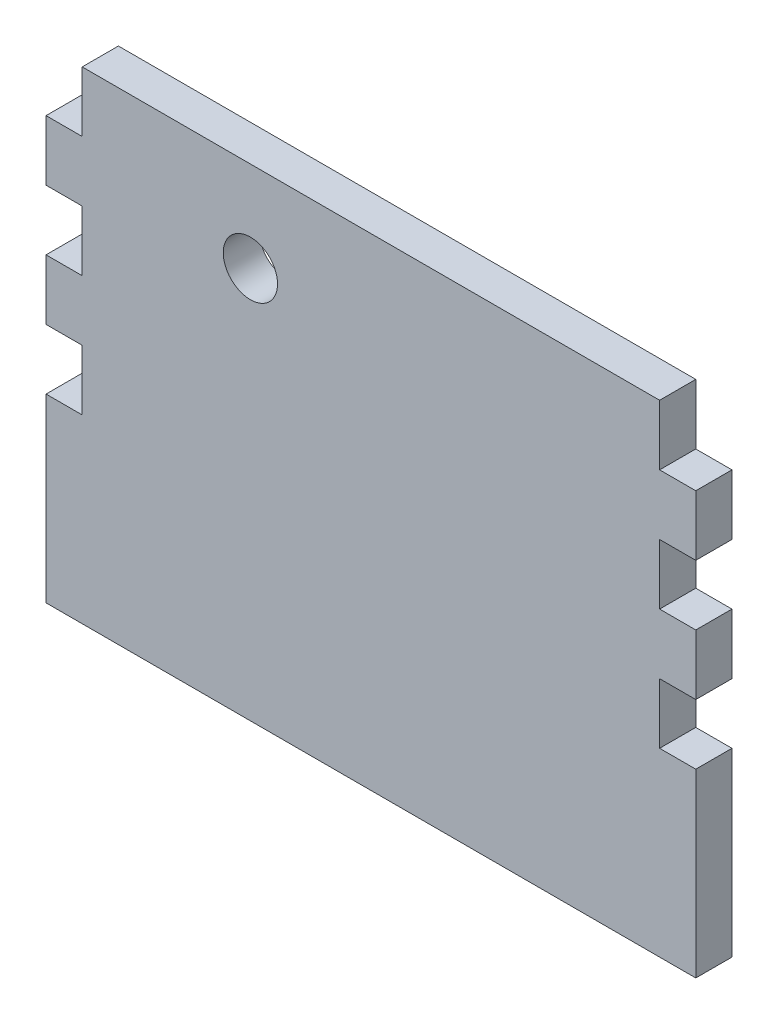
SolidWorks part; units mm, degrees
ref_plane "Front Plane" through (0, 0, 0) normal (0, 0, 1) x (1, 0, 0)
ref_plane "Top Plane" through (0, 0, 0) normal (0, 1, 0) x (1, 0, 0)
ref_plane "Right Plane" through (0, 0, 0) normal (1, 0, 0) x (0, 0, -1)
sketch "Sketch1" plane through (0, 0, 0) normal (0, 0, 1) x (1, 0, 0)
  line L1 (-26.945, 20) -> (26.945, 20)
  line L2 (-26.945, 20) -> (-26.945, -20)
  line L3 (-26.945, -20) -> (26.945, -20)
  line L4 (26.945, 20) -> (26.945, -20)
  line L5 (-26.945, 20) -> (26.945, -20) construction
  line L6 (-26.945, -20) -> (26.945, 20) construction
  point P0 (0, 0)
  dimension "D1" = 53.89
  dimension "D2" = 40
extrude "Boss-Extrude1" add sketch "Sketch1" along normal blind 3 contours L2 L3 L4 L1
sketch "Sketch2" plane through (0, 0, 3) normal (0, 0, 1) x (1, 0, 0)
  line L0 (0, -1.65) -> (0, 1.65) construction
  line L1 (-26.945, 20) -> (-23.945, 20)
  line L2 (-26.945, 20) -> (-26.945, 15)
  line L3 (-26.945, 15) -> (-23.945, 15)
  line L4 (-23.945, 20) -> (-23.945, 15)
  line L5 (-26.945, 5) -> (-23.945, 5)
  line L6 (-26.945, 5) -> (-26.945, 10)
  line L7 (-26.945, 10) -> (-23.945, 10)
  line L8 (-23.945, 5) -> (-23.945, 10)
  line L9 (26.945, 15) -> (23.945, 15)
  line L10 (23.945, 20) -> (23.945, 15)
  line L11 (26.945, 20) -> (23.945, 20)
  line L12 (26.945, 20) -> (26.945, 15)
  line L13 (26.945, 10) -> (23.945, 10)
  line L14 (23.945, 5) -> (23.945, 10)
  line L15 (26.945, 5) -> (23.945, 5)
  line L16 (26.945, 5) -> (26.945, 10)
  line L17 (-26.945, 20) -> (-26.945, -20) construction
  line L18 (-26.945, -20) -> (26.945, -20) construction
  line L19 (26.945, -5) -> (23.945, -5)
  line L20 (-26.945, 0) -> (-23.945, 0)
  line L21 (-26.945, 0) -> (-26.945, -5)
  line L22 (-26.945, -5) -> (-23.945, -5)
  line L23 (-23.945, 0) -> (-23.945, -5)
  line L24 (23.945, 0) -> (23.945, -5)
  line L25 (26.945, 0) -> (23.945, 0)
  line L26 (26.945, 0) -> (26.945, -5)
  circle A0 centre (-9.995, 12.5) radius 2.25
  dimension "D5" = 4.5
  dimension "D1" = 3
  dimension "D2" = 5
  dimension "D3" = 5
  dimension "D4" = 3
  dimension "D6" = 5
  dimension "D7" = 32.5
  dimension "D8" = 16.95
  dimension "D9" = 3
  dimension "D10" = 5
  dimension "D11" = 5
extrude "Cut-Extrude1" cut sketch "Sketch2" against normal blind 3
equation "\"D1@Sketch1\"=47.89 + 6"
equation "\"D3@Sketch2\"=\"D2@Sketch2\""
equation "\"D4@Sketch2\"=\"D1@Sketch2\""
equation "\"D8@Sketch2\"=13.95+\"D1@Sketch2\""
equation "\"D9@Sketch2\"=\"D1@Sketch2\""
equation "\"D10@Sketch2\"=\"D2@Sketch2\""
equation "\"D11@Sketch2\"=\"D6@Sketch2\""
